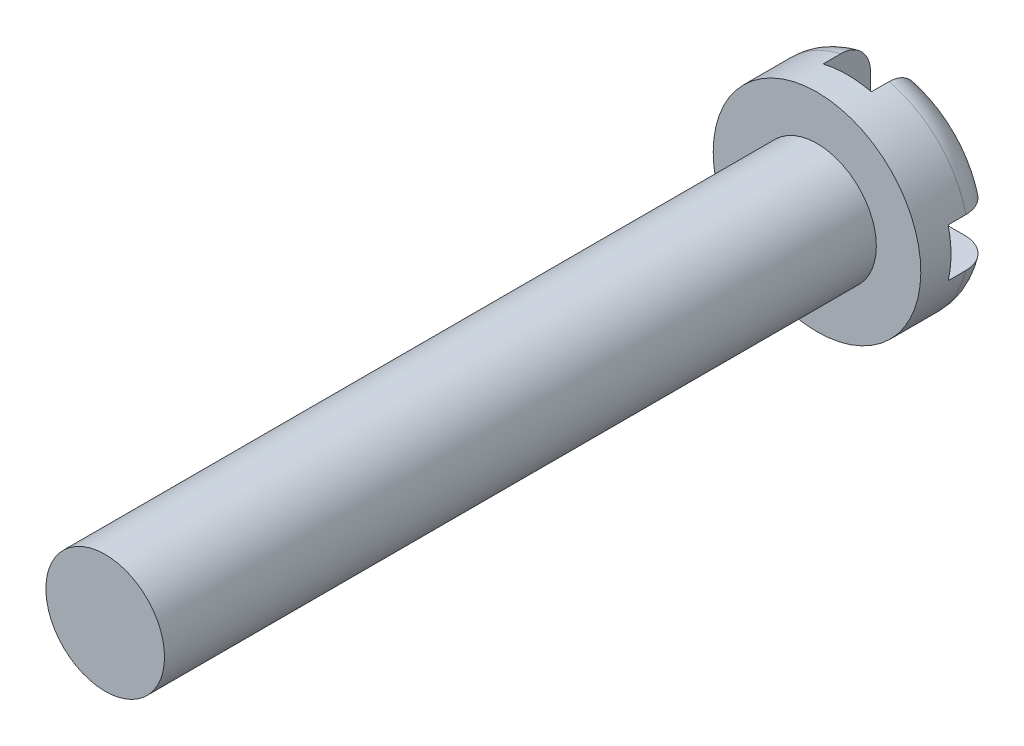
SolidWorks part; units mm, degrees
ref_plane "前视基准面" through (0, 0, 0) normal (0, 0, 1) x (1, 0, 0)
ref_plane "上视基准面" through (0, 0, 0) normal (0, 1, 0) x (1, 0, 0)
ref_plane "右视基准面" through (0, 0, 0) normal (1, 0, 0) x (0, 0, -1)
sketch "草图1" plane through (0, 0, 0) normal (0, 0, 1) x (1, 0, 0)
  circle A0 centre (0, 0) radius 1
extrude "凸台-拉伸1" add sketch "草图1" along normal blind 12
sketch "草图2" plane through (0, 0, 0) normal (0, 0, -1) x (-1, 0, 0)
  circle A0 centre (0, 0) radius 1.75
  dimension "D1" = 3.5
extrude "凸台-拉伸2" add sketch "草图2" along normal blind 1.31
fillet "圆角1" radius 0.5 1 edges at (-1.75, 0, -1.31)
sketch "草图3" plane through (0, 0, -1.31) normal (0, 0, -1) x (-1, 0, 0)
  line L0 (-0.7071, 0.7071) -> (-0.7071, 6.0064) construction
  line L1 (1, -1) -> (-1, -1) construction
  line L2 (1, -1) -> (1, 1) construction
  line L3 (1, 1) -> (-1, 1) construction
  line L4 (-1, -1) -> (-1, 1) construction
  line L5 (1, -1) -> (-1, 1) construction
  line L6 (1, 1) -> (-1, -1) construction
  line L7 (0.7071, 0.7071) -> (0.7071, 6.0064) construction
  line L8 (0.7071, 6.0064) -> (-0.7071, 6.0064) construction
  line L9 (0.7071, 0.7071) -> (6.0064, 0.7071) construction
  line L10 (0.7071, -0.7071) -> (6.0064, -0.7071) construction
  line L11 (6.0064, -0.7071) -> (6.0064, 0.7071) construction
  line L12 (0.7071, -0.7071) -> (0.7071, -6.0064) construction
  line L13 (-0.7071, -0.7071) -> (-0.7071, -6.0064) construction
  line L14 (-0.7071, -6.0064) -> (0.7071, -6.0064) construction
  line L15 (-0.7071, -0.7071) -> (-6.0064, -0.7071) construction
  line L16 (-0.7071, 0.7071) -> (-6.0064, 0.7071) construction
  line L17 (-6.0064, 0.7071) -> (-6.0064, -0.7071) construction
  line L18 (0.4071, 0.4071) -> (0.4071, 5.7064)
  line L19 (0.4071, 5.7064) -> (-0.4071, 5.7064)
  line L20 (-0.4071, 0.4071) -> (-0.4071, 5.7064)
  line L21 (-0.4071, 0.4071) -> (-5.7064, 0.4071)
  line L22 (-5.7064, 0.4071) -> (-5.7064, -0.4071)
  line L23 (-0.4071, -0.4071) -> (-5.7064, -0.4071)
  line L24 (-0.4071, -0.4071) -> (-0.4071, -5.7064)
  line L25 (-0.4071, -5.7064) -> (0.4071, -5.7064)
  line L26 (0.4071, -0.4071) -> (0.4071, -5.7064)
  line L27 (0.4071, -0.4071) -> (5.7064, -0.4071)
  line L28 (5.7064, -0.4071) -> (5.7064, 0.4071)
  line L29 (0.4071, 0.4071) -> (5.7064, 0.4071)
  circle A0 centre (0, 0) radius 1 construction
  dimension "D1" = 4
  dimension "D2" = 0.3
extrude "切除-拉伸1" cut sketch "草图3" against normal blind 0.8
